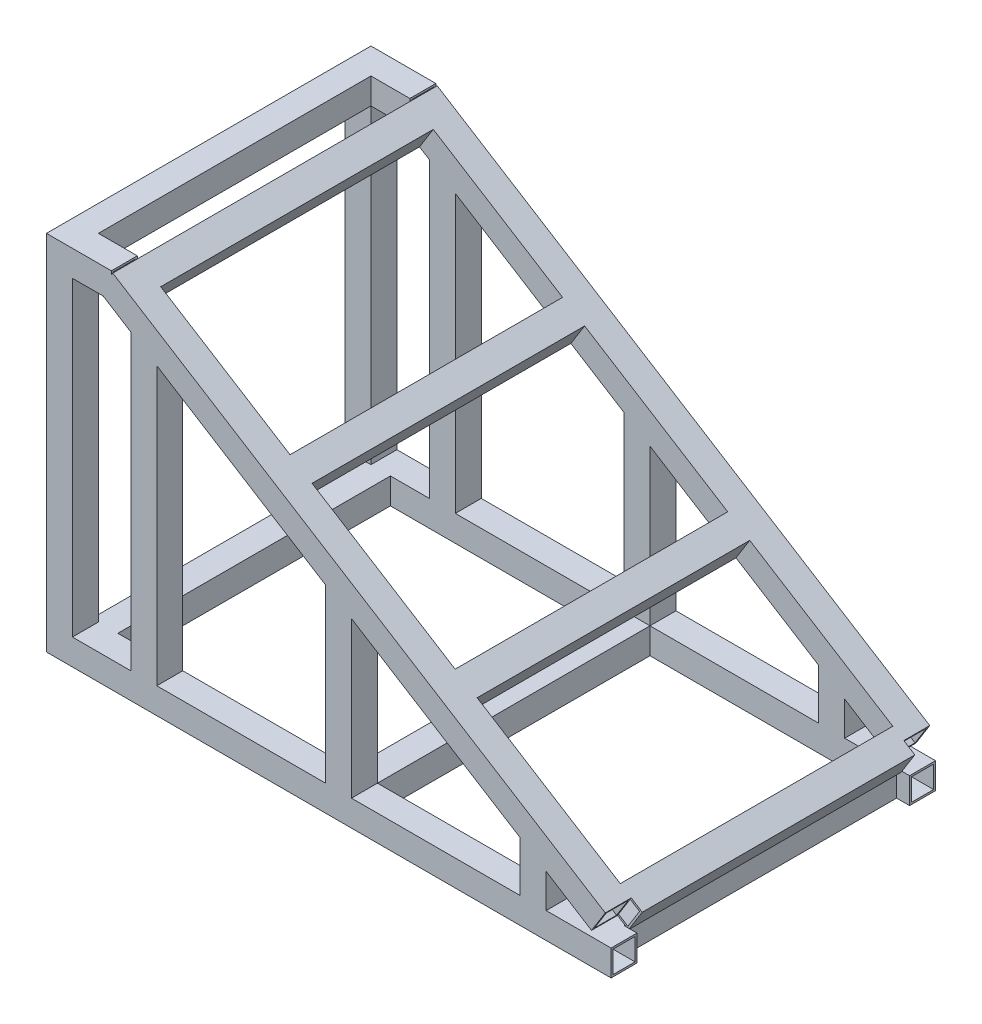
SolidWorks part; units mm, degrees
ref_plane "前视基准面" through (0, 0, 0) normal (0, 0, 1) x (1, 0, 0)
ref_plane "上视基准面" through (0, 0, 0) normal (0, 1, 0) x (1, 0, 0)
ref_plane "右视基准面" through (0, 0, 0) normal (1, 0, 0) x (0, 0, -1)
other "Configuration Table"
sketch "草图1" plane through (0, 0, 0) normal (0, 0, 1) x (1, 0, 0)
  line L0 (50, 0) -> (920, 0)
  line L1 (920, 0) -> (920, 40)
  line L2 (920, 40) -> (50, 40)
  line L3 (50, 40) -> (50, 0)
extrude "L_base_870_skin_A" add sketch "草图1" along normal blind 3
sketch "草图2" plane through (0, 0, 0) normal (0, 0, 1) x (1, 0, 0)
  line L0 (50, 0) -> (920, 0)
  line L1 (920, 0) -> (920, 3)
  line L2 (920, 3) -> (50, 3)
  line L3 (50, 3) -> (50, 0)
  line L4 (50, 37) -> (920, 37)
  line L5 (920, 37) -> (920, 40)
  line L6 (920, 40) -> (50, 40)
  line L7 (50, 40) -> (50, 37)
extrude "L_base_870_edge_walls" add sketch "草图2" along normal blind 34 from offset 3
sketch "草图3" plane through (0, 0, 0) normal (0, 0, 1) x (1, 0, 0)
  line L0 (50, 0) -> (920, 0)
  line L1 (920, 0) -> (920, 40)
  line L2 (920, 40) -> (50, 40)
  line L3 (50, 40) -> (50, 0)
extrude "L_base_870_skin_B" add sketch "草图3" along normal blind 3 from offset 37
sketch "草图4" plane through (0, 0, 0) normal (0, 0, 1) x (1, 0, 0)
  line L0 (130.9238, 522.7884) -> (889.9268, 48.5107)
  line L1 (889.9268, 48.5107) -> (911.1236, 82.4326)
  line L2 (911.1236, 82.4326) -> (152.1206, 556.7103)
  line L3 (152.1206, 556.7103) -> (130.9238, 522.7884)
extrude "L_inclined_895_skin_A" add sketch "草图4" along normal blind 3
sketch "草图5" plane through (0, 0, 0) normal (0, 0, 1) x (1, 0, 0)
  line L0 (130.9238, 522.7884) -> (889.9268, 48.5107)
  line L1 (889.9268, 48.5107) -> (891.5166, 51.0548)
  line L2 (891.5166, 51.0548) -> (132.5136, 525.3326)
  line L3 (132.5136, 525.3326) -> (130.9238, 522.7884)
  line L4 (150.5308, 554.1662) -> (909.5339, 79.8885)
  line L5 (909.5339, 79.8885) -> (911.1236, 82.4326)
  line L6 (911.1236, 82.4326) -> (152.1206, 556.7103)
  line L7 (152.1206, 556.7103) -> (150.5308, 554.1662)
extrude "L_inclined_895_edge_walls" add sketch "草图5" along normal blind 34 from offset 3
sketch "草图6" plane through (0, 0, 0) normal (0, 0, 1) x (1, 0, 0)
  line L0 (130.9238, 522.7884) -> (889.9268, 48.5107)
  line L1 (889.9268, 48.5107) -> (911.1236, 82.4326)
  line L2 (911.1236, 82.4326) -> (152.1206, 556.7103)
  line L3 (152.1206, 556.7103) -> (130.9238, 522.7884)
extrude "L_inclined_895_skin_B" add sketch "草图6" along normal blind 3 from offset 37
sketch "草图7" plane through (0, 0, 0) normal (0, 0, 1) x (1, 0, 0)
  line L0 (50, 518.7521) -> (150, 518.7521)
  line L1 (150, 518.7521) -> (150, 558.7521)
  line L2 (150, 558.7521) -> (50, 558.7521)
  line L3 (50, 558.7521) -> (50, 518.7521)
extrude "L_platform_100_skin_A" add sketch "草图7" along normal blind 3
sketch "草图8" plane through (0, 0, 0) normal (0, 0, 1) x (1, 0, 0)
  line L0 (50, 518.7521) -> (150, 518.7521)
  line L1 (150, 518.7521) -> (150, 521.7521)
  line L2 (150, 521.7521) -> (50, 521.7521)
  line L3 (50, 521.7521) -> (50, 518.7521)
  line L4 (50, 555.7521) -> (150, 555.7521)
  line L5 (150, 555.7521) -> (150, 558.7521)
  line L6 (150, 558.7521) -> (50, 558.7521)
  line L7 (50, 558.7521) -> (50, 555.7521)
extrude "L_platform_100_edge_walls" add sketch "草图8" along normal blind 34 from offset 3
sketch "草图9" plane through (0, 0, 0) normal (0, 0, 1) x (1, 0, 0)
  line L0 (50, 518.7521) -> (150, 518.7521)
  line L1 (150, 518.7521) -> (150, 558.7521)
  line L2 (150, 558.7521) -> (50, 558.7521)
  line L3 (50, 558.7521) -> (50, 518.7521)
extrude "L_platform_100_skin_B" add sketch "草图9" along normal blind 3 from offset 37
sketch "草图10" plane through (0, 0, 0) normal (0, 0, 1) x (1, 0, 0)
  line L0 (50, 40) -> (90, 40)
  line L1 (90, 40) -> (90, 518.7521)
  line L2 (90, 518.7521) -> (50, 518.7521)
  line L3 (50, 518.7521) -> (50, 40)
extrude "L_rear_post_skin_A" add sketch "草图10" along normal blind 3
sketch "草图11" plane through (0, 0, 0) normal (0, 0, 1) x (1, 0, 0)
  line L0 (50, 40) -> (53, 40)
  line L1 (53, 40) -> (53, 518.7521)
  line L2 (53, 518.7521) -> (50, 518.7521)
  line L3 (50, 518.7521) -> (50, 40)
  line L4 (87, 40) -> (90, 40)
  line L5 (90, 40) -> (90, 518.7521)
  line L6 (90, 518.7521) -> (87, 518.7521)
  line L7 (87, 518.7521) -> (87, 40)
extrude "L_rear_post_walls" add sketch "草图11" along normal blind 34 from offset 3
sketch "草图12" plane through (0, 0, 0) normal (0, 0, 1) x (1, 0, 0)
  line L0 (50, 40) -> (90, 40)
  line L1 (90, 40) -> (90, 518.7521)
  line L2 (90, 518.7521) -> (50, 518.7521)
  line L3 (50, 518.7521) -> (50, 40)
extrude "L_rear_post_skin_B" add sketch "草图12" along normal blind 3 from offset 37
sketch "草图13" plane through (0, 0, 0) normal (0, 0, 1) x (1, 0, 0)
  line L0 (180, 40) -> (220, 40)
  line L1 (220, 40) -> (220, 467.1274)
  line L2 (220, 467.1274) -> (180, 492.1222)
  line L3 (180, 492.1222) -> (180, 40)
extrude "L_post_x200_skin_A" add sketch "草图13" along normal blind 3
sketch "草图14" plane through (0, 0, 0) normal (0, 0, 1) x (1, 0, 0)
  line L0 (180, 40) -> (183, 40)
  line L1 (183, 40) -> (183, 490.2476)
  line L2 (183, 490.2476) -> (180, 492.1222)
  line L3 (180, 492.1222) -> (180, 40)
  line L4 (217, 40) -> (220, 40)
  line L5 (220, 40) -> (220, 467.1274)
  line L6 (220, 467.1274) -> (217, 469.002)
  line L7 (217, 469.002) -> (217, 40)
extrude "L_post_x200_walls" add sketch "草图14" along normal blind 34 from offset 3
sketch "草图15" plane through (0, 0, 0) normal (0, 0, 1) x (1, 0, 0)
  line L0 (180, 40) -> (220, 40)
  line L1 (220, 40) -> (220, 467.1274)
  line L2 (220, 467.1274) -> (180, 492.1222)
  line L3 (180, 492.1222) -> (180, 40)
extrude "L_post_x200_skin_B" add sketch "草图15" along normal blind 3 from offset 37
sketch "草图16" plane through (0, 0, 0) normal (0, 0, 1) x (1, 0, 0)
  line L0 (480, 40) -> (520, 40)
  line L1 (520, 40) -> (520, 279.6666)
  line L2 (520, 279.6666) -> (480, 304.6614)
  line L3 (480, 304.6614) -> (480, 40)
extrude "L_post_x500_skin_A" add sketch "草图16" along normal blind 3
sketch "草图17" plane through (0, 0, 0) normal (0, 0, 1) x (1, 0, 0)
  line L0 (480, 40) -> (483, 40)
  line L1 (483, 40) -> (483, 302.7868)
  line L2 (483, 302.7868) -> (480, 304.6614)
  line L3 (480, 304.6614) -> (480, 40)
  line L4 (517, 40) -> (520, 40)
  line L5 (520, 40) -> (520, 279.6666)
  line L6 (520, 279.6666) -> (517, 281.5412)
  line L7 (517, 281.5412) -> (517, 40)
extrude "L_post_x500_walls" add sketch "草图17" along normal blind 34 from offset 3
sketch "草图18" plane through (0, 0, 0) normal (0, 0, 1) x (1, 0, 0)
  line L0 (480, 40) -> (520, 40)
  line L1 (520, 40) -> (520, 279.6666)
  line L2 (520, 279.6666) -> (480, 304.6614)
  line L3 (480, 304.6614) -> (480, 40)
extrude "L_post_x500_skin_B" add sketch "草图18" along normal blind 3 from offset 37
sketch "草图19" plane through (0, 0, 0) normal (0, 0, 1) x (1, 0, 0)
  line L0 (780, 40) -> (820, 40)
  line L1 (820, 40) -> (820, 92.2058)
  line L2 (820, 92.2058) -> (780, 117.2006)
  line L3 (780, 117.2006) -> (780, 40)
extrude "L_post_x800_skin_A" add sketch "草图19" along normal blind 3
sketch "草图20" plane through (0, 0, 0) normal (0, 0, 1) x (1, 0, 0)
  line L0 (780, 40) -> (783, 40)
  line L1 (783, 40) -> (783, 115.326)
  line L2 (783, 115.326) -> (780, 117.2006)
  line L3 (780, 117.2006) -> (780, 40)
  line L4 (817, 40) -> (820, 40)
  line L5 (820, 40) -> (820, 92.2058)
  line L6 (820, 92.2058) -> (817, 94.0804)
  line L7 (817, 94.0804) -> (817, 40)
extrude "L_post_x800_walls" add sketch "草图20" along normal blind 34 from offset 3
sketch "草图21" plane through (0, 0, 0) normal (0, 0, 1) x (1, 0, 0)
  line L0 (780, 40) -> (820, 40)
  line L1 (820, 40) -> (820, 92.2058)
  line L2 (820, 92.2058) -> (780, 117.2006)
  line L3 (780, 117.2006) -> (780, 40)
extrude "L_post_x800_skin_B" add sketch "草图21" along normal blind 3 from offset 37
sketch "草图22" plane through (0, 0, 0) normal (0, 0, 1) x (1, 0, 0)
  line L0 (50, 0) -> (920, 0)
  line L1 (920, 0) -> (920, 40)
  line L2 (920, 40) -> (50, 40)
  line L3 (50, 40) -> (50, 0)
extrude "R_base_870_skin_A" add sketch "草图22" along normal blind 3 from offset 460
sketch "草图23" plane through (0, 0, 0) normal (0, 0, 1) x (1, 0, 0)
  line L0 (50, 0) -> (920, 0)
  line L1 (920, 0) -> (920, 3)
  line L2 (920, 3) -> (50, 3)
  line L3 (50, 3) -> (50, 0)
  line L4 (50, 37) -> (920, 37)
  line L5 (920, 37) -> (920, 40)
  line L6 (920, 40) -> (50, 40)
  line L7 (50, 40) -> (50, 37)
extrude "R_base_870_edge_walls" add sketch "草图23" along normal blind 34 from offset 463
sketch "草图24" plane through (0, 0, 0) normal (0, 0, 1) x (1, 0, 0)
  line L0 (50, 0) -> (920, 0)
  line L1 (920, 0) -> (920, 40)
  line L2 (920, 40) -> (50, 40)
  line L3 (50, 40) -> (50, 0)
extrude "R_base_870_skin_B" add sketch "草图24" along normal blind 3 from offset 497
sketch "草图25" plane through (0, 0, 0) normal (0, 0, 1) x (1, 0, 0)
  line L0 (130.9238, 522.7884) -> (889.9268, 48.5107)
  line L1 (889.9268, 48.5107) -> (911.1236, 82.4326)
  line L2 (911.1236, 82.4326) -> (152.1206, 556.7103)
  line L3 (152.1206, 556.7103) -> (130.9238, 522.7884)
extrude "R_inclined_895_skin_A" add sketch "草图25" along normal blind 3 from offset 460
sketch "草图26" plane through (0, 0, 0) normal (0, 0, 1) x (1, 0, 0)
  line L0 (130.9238, 522.7884) -> (889.9268, 48.5107)
  line L1 (889.9268, 48.5107) -> (891.5166, 51.0548)
  line L2 (891.5166, 51.0548) -> (132.5136, 525.3326)
  line L3 (132.5136, 525.3326) -> (130.9238, 522.7884)
  line L4 (150.5308, 554.1662) -> (909.5339, 79.8885)
  line L5 (909.5339, 79.8885) -> (911.1236, 82.4326)
  line L6 (911.1236, 82.4326) -> (152.1206, 556.7103)
  line L7 (152.1206, 556.7103) -> (150.5308, 554.1662)
extrude "R_inclined_895_edge_walls" add sketch "草图26" along normal blind 34 from offset 463
sketch "草图27" plane through (0, 0, 0) normal (0, 0, 1) x (1, 0, 0)
  line L0 (130.9238, 522.7884) -> (889.9268, 48.5107)
  line L1 (889.9268, 48.5107) -> (911.1236, 82.4326)
  line L2 (911.1236, 82.4326) -> (152.1206, 556.7103)
  line L3 (152.1206, 556.7103) -> (130.9238, 522.7884)
extrude "R_inclined_895_skin_B" add sketch "草图27" along normal blind 3 from offset 497
sketch "草图28" plane through (0, 0, 0) normal (0, 0, 1) x (1, 0, 0)
  line L0 (50, 518.7521) -> (150, 518.7521)
  line L1 (150, 518.7521) -> (150, 558.7521)
  line L2 (150, 558.7521) -> (50, 558.7521)
  line L3 (50, 558.7521) -> (50, 518.7521)
extrude "R_platform_100_skin_A" add sketch "草图28" along normal blind 3 from offset 460
sketch "草图29" plane through (0, 0, 0) normal (0, 0, 1) x (1, 0, 0)
  line L0 (50, 518.7521) -> (150, 518.7521)
  line L1 (150, 518.7521) -> (150, 521.7521)
  line L2 (150, 521.7521) -> (50, 521.7521)
  line L3 (50, 521.7521) -> (50, 518.7521)
  line L4 (50, 555.7521) -> (150, 555.7521)
  line L5 (150, 555.7521) -> (150, 558.7521)
  line L6 (150, 558.7521) -> (50, 558.7521)
  line L7 (50, 558.7521) -> (50, 555.7521)
extrude "R_platform_100_edge_walls" add sketch "草图29" along normal blind 34 from offset 463
sketch "草图30" plane through (0, 0, 0) normal (0, 0, 1) x (1, 0, 0)
  line L0 (50, 518.7521) -> (150, 518.7521)
  line L1 (150, 518.7521) -> (150, 558.7521)
  line L2 (150, 558.7521) -> (50, 558.7521)
  line L3 (50, 558.7521) -> (50, 518.7521)
extrude "R_platform_100_skin_B" add sketch "草图30" along normal blind 3 from offset 497
sketch "草图31" plane through (0, 0, 0) normal (0, 0, 1) x (1, 0, 0)
  line L0 (50, 40) -> (90, 40)
  line L1 (90, 40) -> (90, 518.7521)
  line L2 (90, 518.7521) -> (50, 518.7521)
  line L3 (50, 518.7521) -> (50, 40)
extrude "R_rear_post_skin_A" add sketch "草图31" along normal blind 3 from offset 460
sketch "草图32" plane through (0, 0, 0) normal (0, 0, 1) x (1, 0, 0)
  line L0 (50, 40) -> (53, 40)
  line L1 (53, 40) -> (53, 518.7521)
  line L2 (53, 518.7521) -> (50, 518.7521)
  line L3 (50, 518.7521) -> (50, 40)
  line L4 (87, 40) -> (90, 40)
  line L5 (90, 40) -> (90, 518.7521)
  line L6 (90, 518.7521) -> (87, 518.7521)
  line L7 (87, 518.7521) -> (87, 40)
extrude "R_rear_post_walls" add sketch "草图32" along normal blind 34 from offset 463
sketch "草图33" plane through (0, 0, 0) normal (0, 0, 1) x (1, 0, 0)
  line L0 (50, 40) -> (90, 40)
  line L1 (90, 40) -> (90, 518.7521)
  line L2 (90, 518.7521) -> (50, 518.7521)
  line L3 (50, 518.7521) -> (50, 40)
extrude "R_rear_post_skin_B" add sketch "草图33" along normal blind 3 from offset 497
sketch "草图34" plane through (0, 0, 0) normal (0, 0, 1) x (1, 0, 0)
  line L0 (180, 40) -> (220, 40)
  line L1 (220, 40) -> (220, 467.1274)
  line L2 (220, 467.1274) -> (180, 492.1222)
  line L3 (180, 492.1222) -> (180, 40)
extrude "R_post_x200_skin_A" add sketch "草图34" along normal blind 3 from offset 460
sketch "草图35" plane through (0, 0, 0) normal (0, 0, 1) x (1, 0, 0)
  line L0 (180, 40) -> (183, 40)
  line L1 (183, 40) -> (183, 490.2476)
  line L2 (183, 490.2476) -> (180, 492.1222)
  line L3 (180, 492.1222) -> (180, 40)
  line L4 (217, 40) -> (220, 40)
  line L5 (220, 40) -> (220, 467.1274)
  line L6 (220, 467.1274) -> (217, 469.002)
  line L7 (217, 469.002) -> (217, 40)
extrude "R_post_x200_walls" add sketch "草图35" along normal blind 34 from offset 463
sketch "草图36" plane through (0, 0, 0) normal (0, 0, 1) x (1, 0, 0)
  line L0 (180, 40) -> (220, 40)
  line L1 (220, 40) -> (220, 467.1274)
  line L2 (220, 467.1274) -> (180, 492.1222)
  line L3 (180, 492.1222) -> (180, 40)
extrude "R_post_x200_skin_B" add sketch "草图36" along normal blind 3 from offset 497
sketch "草图37" plane through (0, 0, 0) normal (0, 0, 1) x (1, 0, 0)
  line L0 (480, 40) -> (520, 40)
  line L1 (520, 40) -> (520, 279.6666)
  line L2 (520, 279.6666) -> (480, 304.6614)
  line L3 (480, 304.6614) -> (480, 40)
extrude "R_post_x500_skin_A" add sketch "草图37" along normal blind 3 from offset 460
sketch "草图38" plane through (0, 0, 0) normal (0, 0, 1) x (1, 0, 0)
  line L0 (480, 40) -> (483, 40)
  line L1 (483, 40) -> (483, 302.7868)
  line L2 (483, 302.7868) -> (480, 304.6614)
  line L3 (480, 304.6614) -> (480, 40)
  line L4 (517, 40) -> (520, 40)
  line L5 (520, 40) -> (520, 279.6666)
  line L6 (520, 279.6666) -> (517, 281.5412)
  line L7 (517, 281.5412) -> (517, 40)
extrude "R_post_x500_walls" add sketch "草图38" along normal blind 34 from offset 463
sketch "草图39" plane through (0, 0, 0) normal (0, 0, 1) x (1, 0, 0)
  line L0 (480, 40) -> (520, 40)
  line L1 (520, 40) -> (520, 279.6666)
  line L2 (520, 279.6666) -> (480, 304.6614)
  line L3 (480, 304.6614) -> (480, 40)
extrude "R_post_x500_skin_B" add sketch "草图39" along normal blind 3 from offset 497
sketch "草图40" plane through (0, 0, 0) normal (0, 0, 1) x (1, 0, 0)
  line L0 (780, 40) -> (820, 40)
  line L1 (820, 40) -> (820, 92.2058)
  line L2 (820, 92.2058) -> (780, 117.2006)
  line L3 (780, 117.2006) -> (780, 40)
extrude "R_post_x800_skin_A" add sketch "草图40" along normal blind 3 from offset 460
sketch "草图41" plane through (0, 0, 0) normal (0, 0, 1) x (1, 0, 0)
  line L0 (780, 40) -> (783, 40)
  line L1 (783, 40) -> (783, 115.326)
  line L2 (783, 115.326) -> (780, 117.2006)
  line L3 (780, 117.2006) -> (780, 40)
  line L4 (817, 40) -> (820, 40)
  line L5 (820, 40) -> (820, 92.2058)
  line L6 (820, 92.2058) -> (817, 94.0804)
  line L7 (817, 94.0804) -> (817, 40)
extrude "R_post_x800_walls" add sketch "草图41" along normal blind 34 from offset 463
sketch "草图42" plane through (0, 0, 0) normal (0, 0, 1) x (1, 0, 0)
  line L0 (780, 40) -> (820, 40)
  line L1 (820, 40) -> (820, 92.2058)
  line L2 (820, 92.2058) -> (780, 117.2006)
  line L3 (780, 117.2006) -> (780, 40)
extrude "R_post_x800_skin_B" add sketch "草图42" along normal blind 3 from offset 497
sketch "草图43" plane through (0, 0, 0) normal (0, 0, 1) x (1, 0, 0)
  line L0 (130.9238, 522.7884) -> (164.8457, 501.5916)
  line L1 (164.8457, 501.5916) -> (186.0425, 535.5136)
  line L2 (186.0425, 535.5136) -> (152.1206, 556.7103)
  line L3 (152.1206, 556.7103) -> (130.9238, 522.7884)
  line L4 (135.0577, 523.7428) -> (163.8913, 505.7255)
  line L5 (163.8913, 505.7255) -> (181.9086, 534.5592)
  line L6 (181.9086, 534.5592) -> (153.0749, 552.5764)
  line L7 (153.0749, 552.5764) -> (135.0577, 523.7428)
extrude "Transverse_s25_420" add sketch "草图43" along normal blind 420 from offset 40
sketch "草图44" plane through (0, 0, 0) normal (0, 0, 1) x (1, 0, 0)
  line L0 (364.137, 377.0606) -> (398.0589, 355.8638)
  line L1 (398.0589, 355.8638) -> (419.2557, 389.7858)
  line L2 (419.2557, 389.7858) -> (385.3338, 410.9825)
  line L3 (385.3338, 410.9825) -> (364.137, 377.0606)
  line L4 (368.2709, 378.015) -> (397.1046, 359.9977)
  line L5 (397.1046, 359.9977) -> (415.1218, 388.8314)
  line L6 (415.1218, 388.8314) -> (386.2882, 406.8486)
  line L7 (386.2882, 406.8486) -> (368.2709, 378.015)
extrude "Transverse_s300_420" add sketch "草图44" along normal blind 420 from offset 40
sketch "草图45" plane through (0, 0, 0) normal (0, 0, 1) x (1, 0, 0)
  line L0 (618.5514, 218.0848) -> (652.4734, 196.8881)
  line L1 (652.4734, 196.8881) -> (673.6701, 230.81)
  line L2 (673.6701, 230.81) -> (639.7482, 252.0068)
  line L3 (639.7482, 252.0068) -> (618.5514, 218.0848)
  line L4 (622.6854, 219.0392) -> (651.519, 201.022)
  line L5 (651.519, 201.022) -> (669.5362, 229.8556)
  line L6 (669.5362, 229.8556) -> (640.7026, 247.8729)
  line L7 (640.7026, 247.8729) -> (622.6854, 219.0392)
extrude "Transverse_s600_420" add sketch "草图45" along normal blind 420 from offset 40
sketch "草图46" plane through (0, 0, 0) normal (0, 0, 1) x (1, 0, 0)
  line L0 (872.9659, 59.1091) -> (906.8878, 37.9123)
  line L1 (906.8878, 37.9123) -> (928.0846, 71.8342)
  line L2 (928.0846, 71.8342) -> (894.1626, 93.031)
  line L3 (894.1626, 93.031) -> (872.9659, 59.1091)
  line L4 (877.0998, 60.0634) -> (905.9334, 42.0462)
  line L5 (905.9334, 42.0462) -> (923.9507, 70.8798)
  line L6 (923.9507, 70.8798) -> (895.117, 88.8971)
  line L7 (895.117, 88.8971) -> (877.0998, 60.0634)
extrude "Transverse_s900_420" add sketch "草图46" along normal blind 420 from offset 40
sketch "草图47" plane through (0, 0, 0) normal (0, 0, 1) x (1, 0, 0)
  line L0 (80, 0) -> (120, 0)
  line L1 (120, 0) -> (120, 40)
  line L2 (120, 40) -> (80, 40)
  line L3 (80, 40) -> (80, 0)
  line L4 (83, 3) -> (117, 3)
  line L5 (117, 3) -> (117, 37)
  line L6 (117, 37) -> (83, 37)
  line L7 (83, 37) -> (83, 3)
extrude "Base_transverse_x100_420" add sketch "草图47" along normal blind 420 from offset 40
sketch "草图48" plane through (0, 0, 0) normal (0, 0, 1) x (1, 0, 0)
  line L0 (480, 0) -> (520, 0)
  line L1 (520, 0) -> (520, 40)
  line L2 (520, 40) -> (480, 40)
  line L3 (480, 40) -> (480, 0)
  line L4 (483, 3) -> (517, 3)
  line L5 (517, 3) -> (517, 37)
  line L6 (517, 37) -> (483, 37)
  line L7 (483, 37) -> (483, 3)
extrude "Base_transverse_x500_420" add sketch "草图48" along normal blind 420 from offset 40
sketch "草图49" plane through (0, 0, 0) normal (0, 0, 1) x (1, 0, 0)
  line L0 (860, 0) -> (900, 0)
  line L1 (900, 0) -> (900, 40)
  line L2 (900, 40) -> (860, 40)
  line L3 (860, 40) -> (860, 0)
  line L4 (863, 3) -> (897, 3)
  line L5 (897, 3) -> (897, 37)
  line L6 (897, 37) -> (863, 37)
  line L7 (863, 37) -> (863, 3)
extrude "Base_transverse_x880_420" add sketch "草图49" along normal blind 420 from offset 40
sketch "草图50" plane through (0, 0, 0) normal (0, 0, 1) x (1, 0, 0)
  line L0 (50, 518.7521) -> (90, 518.7521)
  line L1 (90, 518.7521) -> (90, 558.7521)
  line L2 (90, 558.7521) -> (50, 558.7521)
  line L3 (50, 558.7521) -> (50, 518.7521)
  line L4 (53, 521.7521) -> (87, 521.7521)
  line L5 (87, 521.7521) -> (87, 555.7521)
  line L6 (87, 555.7521) -> (53, 555.7521)
  line L7 (53, 555.7521) -> (53, 521.7521)
extrude "Platform_cross_tie_420" add sketch "草图50" along normal blind 420 from offset 40
